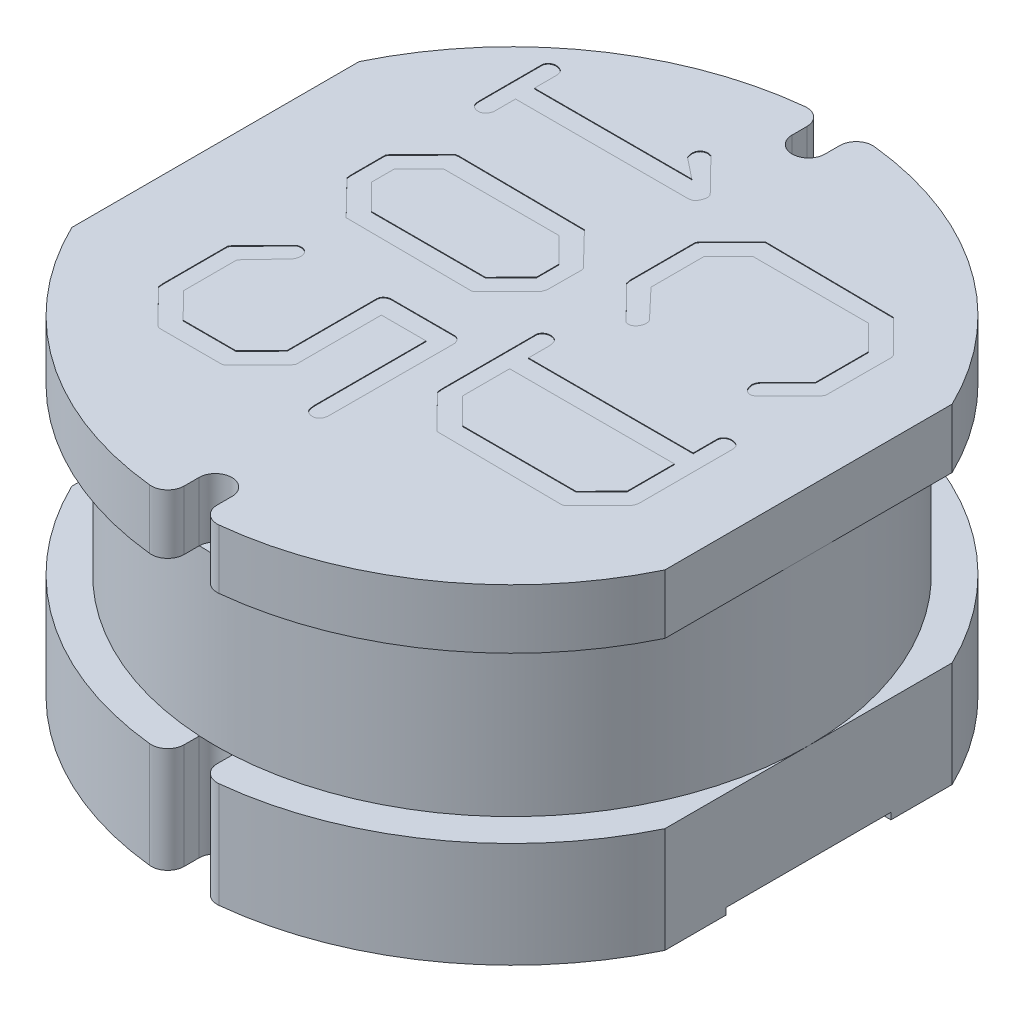
SolidWorks part; units mm, degrees
ref_plane "Front Plane" through (0, 0, 0) normal (0, 0, 1) x (1, 0, 0)
ref_plane "Top Plane" through (0, 0, 0) normal (0, 1, 0) x (1, 0, 0)
ref_plane "Right Plane" through (0, 0, 0) normal (1, 0, 0) x (0, 0, -1)
sketch "Sketch1" plane through (0, 0, 0) normal (0, 1, 0) x (1, 0, 0)
  line L0 (0, 10.5332) -> (0, 5) construction
  line L1 (-11.6124, 0) -> (-5, 0) construction
  line L2 (-4.5, 2.1794) -> (-4.5, -2.1794)
  line L3 (4.5, 2.1794) -> (4.5, -2.1794)
  line L4 (-5, 0) -> (-4.5, 0) construction
  line L5 (-4.5, 0) -> (4.5, 0) construction
  line L6 (4.5, 0) -> (5, 0) construction
  line L7 (5, 0) -> (12.0455, 0) construction
  line L8 (-0.25, 4.5) -> (-0.25, 4.7236)
  line L9 (0.25, 4.5) -> (0.25, 4.7236)
  line L10 (0, 5) -> (0, 4.25) construction
  line L11 (0, 4.25) -> (0, -4.25) construction
  line L12 (-0.25, -4.5) -> (-0.25, -4.7236)
  line L13 (0.25, -4.5) -> (0.25, -4.7236)
  line L14 (0, -4.25) -> (0, -5) construction
  line L15 (0, -5) -> (0, -14.4615) construction
  arc A0 (-4.5, -2.1794) -> (-0.5263, -4.9722) centre (0, 0) ccw
  arc A1 (-4.5, 2.1794) -> (-5, 0) centre (0, 0) ccw construction
  arc A2 (-5, 0) -> (-4.5, -2.1794) centre (0, 0) ccw construction
  arc A3 (5, 0) -> (4.5, 2.1794) centre (0, 0) ccw construction
  arc A4 (4.5, 2.1794) -> (0.5263, 4.9722) centre (0, 0) ccw
  arc A5 (4.5, -2.1794) -> (5, 0) centre (0, 0) ccw construction
  arc A6 (-0.25, 4.5) -> (0.25, 4.5) centre (0, 4.5) ccw
  arc A7 (-0.25, 4.7236) -> (-0.5263, 4.9722) centre (-0.5, 4.7236) ccw
  arc A8 (0.25, 4.7236) -> (0.5263, 4.9722) centre (0.5, 4.7236) cw
  arc A9 (0.5263, 4.9722) -> (0, 5) centre (0, 0) ccw construction
  arc A10 (-0.5263, 4.9722) -> (-4.5, 2.1794) centre (0, 0) ccw
  arc A11 (0, 5) -> (-0.5263, 4.9722) centre (0, 0) ccw construction
  arc A12 (-0.25, -4.7236) -> (-0.5263, -4.9722) centre (-0.5, -4.7236) cw
  arc A13 (-0.25, -4.5) -> (0.25, -4.5) centre (0, -4.5) cw
  arc A14 (0.25, -4.7236) -> (0.5263, -4.9722) centre (0.5, -4.7236) ccw
  arc A15 (-0.5263, -4.9722) -> (0, -5) centre (0, 0) ccw construction
  arc A16 (0.5263, -4.9722) -> (4.5, -2.1794) centre (0, 0) ccw
  arc A17 (0, -5) -> (0.5263, -4.9722) centre (0, 0) ccw construction
  dimension "D2" = 10
  dimension "D5" = 0.25
  dimension "D1" = 9
  dimension "D3" = 0.5
  dimension "D4" = 0.5
extrude "Boss-Extrude1" add sketch "Sketch1" along normal blind 1.5
sketch "Sketch2" plane through (0, 1.5, 0) normal (0, 1, 0) x (1, 0, 0)
  circle A0 centre (0, 0) radius 4.5
  dimension "D1" = 9
extrude "Boss-Extrude2" add sketch "Sketch2" along normal blind 2.5
sketch "Sketch3" plane through (0, 4, 0) normal (0, 1, 0) x (1, 0, 0)
  line L0 (-4.5, 2.1794) -> (-4.5, -2.1794) construction
  line L1 (-0.25, 4.5) -> (-0.25, 4.7236) construction
  line L2 (0.25, 4.5) -> (0.25, 4.7236) construction
  line L3 (4.5, 2.1794) -> (4.5, -2.1794) construction
  line L4 (0.25, -4.5) -> (0.25, -4.7236) construction
  line L5 (-0.25, -4.5) -> (-0.25, -4.7236) construction
  line L6 (-4.5, 2.1794) -> (-4.5, -2.1794)
  line L7 (-0.25, 4.5) -> (-0.25, 4.7236)
  line L8 (0.25, 4.5) -> (0.25, 4.7236)
  line L9 (4.5, 2.1794) -> (4.5, -2.1794)
  line L10 (0.25, -4.5) -> (0.25, -4.7236)
  line L11 (-0.25, -4.5) -> (-0.25, -4.7236)
  arc A0 (-0.5263, 4.9722) -> (-4.5, 2.1794) centre (0, 0) ccw construction
  arc A1 (-0.25, 4.7236) -> (-0.5263, 4.9722) centre (-0.5, 4.7236) ccw construction
  arc A2 (-0.25, 4.5) -> (0.25, 4.5) centre (0, 4.5) ccw construction
  arc A3 (0.5263, 4.9722) -> (0.25, 4.7236) centre (0.5, 4.7236) ccw construction
  arc A4 (4.5, 2.1794) -> (0.5263, 4.9722) centre (0, 0) ccw construction
  arc A5 (0.5263, -4.9722) -> (4.5, -2.1794) centre (0, 0) ccw construction
  arc A6 (0.25, -4.7236) -> (0.5263, -4.9722) centre (0.5, -4.7236) ccw construction
  arc A7 (0.25, -4.5) -> (-0.25, -4.5) centre (0, -4.5) ccw construction
  arc A8 (-0.5263, -4.9722) -> (-0.25, -4.7236) centre (-0.5, -4.7236) ccw construction
  arc A9 (-4.5, -2.1794) -> (-0.5263, -4.9722) centre (0, 0) ccw construction
  arc A10 (-0.5263, 4.9722) -> (-4.5, 2.1794) centre (0, 0) ccw
  arc A11 (-0.25, 4.7236) -> (-0.5263, 4.9722) centre (-0.5, 4.7236) ccw
  arc A12 (-0.25, 4.5) -> (0.25, 4.5) centre (0, 4.5) ccw
  arc A13 (0.5263, 4.9722) -> (0.25, 4.7236) centre (0.5, 4.7236) ccw
  arc A14 (4.5, 2.1794) -> (0.5263, 4.9722) centre (0, 0) ccw
  arc A15 (0.5263, -4.9722) -> (4.5, -2.1794) centre (0, 0) ccw
  arc A16 (0.25, -4.7236) -> (0.5263, -4.9722) centre (0.5, -4.7236) ccw
  arc A17 (0.25, -4.5) -> (-0.25, -4.5) centre (0, -4.5) ccw
  arc A18 (-0.5263, -4.9722) -> (-0.25, -4.7236) centre (-0.5, -4.7236) ccw
  arc A19 (-4.5, -2.1794) -> (-0.5263, -4.9722) centre (0, 0) ccw
extrude "Boss-Extrude3" add sketch "Sketch3" along normal blind 0.9
sketch "Sketch4" plane through (0, 0, 0) normal (0, -1, 0) x (1, 0, 0)
  line L0 (-4.5, 1.25) -> (4.5, 1.25)
  line L1 (-4.5, -2.1794) -> (-4.5, 2.1794) construction
  line L2 (4.5, -2.1794) -> (4.5, 2.1794) construction
  line L3 (4.5, 1.25) -> (4.5, 2.1794)
  line L4 (0.25, 4.5) -> (0.25, 4.7236) construction
  line L5 (0.25, 4.5) -> (0.25, 4.7236)
  line L6 (-4.5, 2.1794) -> (-4.5, 1.25)
  line L7 (-4.5, 0) -> (4.5, 0) construction
  line L8 (0, 0) -> (-5, 0) construction
  line L9 (0.25, -4.5) -> (0.25, -4.7236)
  line L10 (4.5, -1.25) -> (4.5, -2.1794)
  line L11 (-4.5, -1.25) -> (4.5, -1.25)
  line L12 (-4.5, -2.1794) -> (-4.5, -1.25)
  arc A0 (-0.5263, 4.9722) -> (-4.5, 2.1794) centre (0, 0) ccw construction
  arc A1 (-0.25, 4.7236) -> (-0.5263, 4.9722) centre (-0.5, 4.7236) ccw construction
  arc A2 (-0.25, 4.5) -> (0.25, 4.5) centre (0, 4.5) ccw construction
  arc A3 (0.5263, 4.9722) -> (0.25, 4.7236) centre (0.5, 4.7236) ccw construction
  arc A4 (4.5, 2.1794) -> (0.5263, 4.9722) centre (0, 0) ccw construction
  arc A5 (-0.5263, 4.9722) -> (-4.5, 2.1794) centre (0, 0) ccw
  arc A6 (-0.25, 4.7236) -> (-0.5263, 4.9722) centre (-0.5, 4.7236) ccw
  arc A7 (-0.25, 4.5) -> (0.25, 4.5) centre (0, 4.5) ccw
  arc A8 (0.5263, 4.9722) -> (0.25, 4.7236) centre (0.5, 4.7236) ccw
  arc A9 (4.5, 2.1794) -> (0.5263, 4.9722) centre (0, 0) ccw
  arc A10 (-0.25, -4.5) -> (0.25, -4.5) centre (0, -4.5) cw
  arc A11 (0.5263, -4.9722) -> (0.25, -4.7236) centre (0.5, -4.7236) cw
  arc A12 (4.5, -2.1794) -> (0.5263, -4.9722) centre (0, 0) cw
  arc A13 (-0.5263, -4.9722) -> (-4.5, -2.1794) centre (0, 0) cw
  arc A14 (-0.25, -4.7236) -> (-0.5263, -4.9722) centre (-0.5, -4.7236) cw
  arc M3 (-4.5, -2.1794) -> (-0.5263, -4.9722) centre (0, 0) ccw
  arc M4 (-0.5263, -4.9722) -> (-0.25, -4.7236) centre (-0.5, -4.7236) ccw
  line M5 (-0.25, -4.7236) -> (-0.25, -4.5)
  arc M6 (-0.25, -4.5) -> (0.25, -4.5) centre (0, -4.5) cw
  line M7 (0.25, -4.5) -> (0.25, -4.7236)
  arc M8 (0.25, -4.7236) -> (0.5263, -4.9722) centre (0.5, -4.7236) ccw
  arc M9 (0.5263, -4.9722) -> (4.5, -2.1794) centre (0, 0) ccw
  line M10 (4.5, -2.1794) -> (4.5, 2.1794)
  arc M11 (4.5, 2.1794) -> (0.5263, 4.9722) centre (0, 0) ccw
  arc M12 (0.5263, 4.9722) -> (0.25, 4.7236) centre (0.5, 4.7236) ccw
  line M13 (0.25, 4.7236) -> (0.25, 4.5)
  arc M14 (0.25, 4.5) -> (-0.25, 4.5) centre (0, 4.5) cw
  line M15 (-0.25, 4.5) -> (-0.25, 4.7236)
  arc M16 (-0.25, 4.7236) -> (-0.5263, 4.9722) centre (-0.5, 4.7236) ccw
  arc M17 (-0.5263, 4.9722) -> (-4.5, 2.1794) centre (0, 0) ccw
  line M18 (-4.5, 2.1794) -> (-4.5, -2.1794)
  dimension "D1" = 1.25
extrude "Boss-Extrude4" add sketch "Sketch4" along normal blind 0.1 contours L0 M18 M10 M11 M12 M13 M14 M15 M16 M17 | L11 M18 M3 M4 M5 M6 M7 M8 M9 M10
sketch "Sketch6" plane through (0, 4.9, 0) normal (0, 1, 0) x (1, 0, 0)
  line L0 (0.5, 4.4736) -> (0.5, -4.4736) construction
  line L1 (-3, 4.4736) -> (-3, -4.4736) construction
  line L2 (4.5, -2.1794) -> (4.5, 2.1794) construction
  line L3 (-4.5, 0) -> (4.5, 0) construction
  line L4 (-4.5, 2.1794) -> (-4.5, -2.1794) construction
  arc A0 (0.5263, 4.9722) -> (0.25, 4.7236) centre (0.5, 4.7236) ccw construction
  text T0 "CD" font "SWTxt" height 3
  text T1 "105\r\n" font "SWTxt" height 3
  dimension "D1" = 4
  dimension "D2" = 7.5
extrude "Cut-Extrude1" cut sketch "Sketch6" against normal blind 0.01
